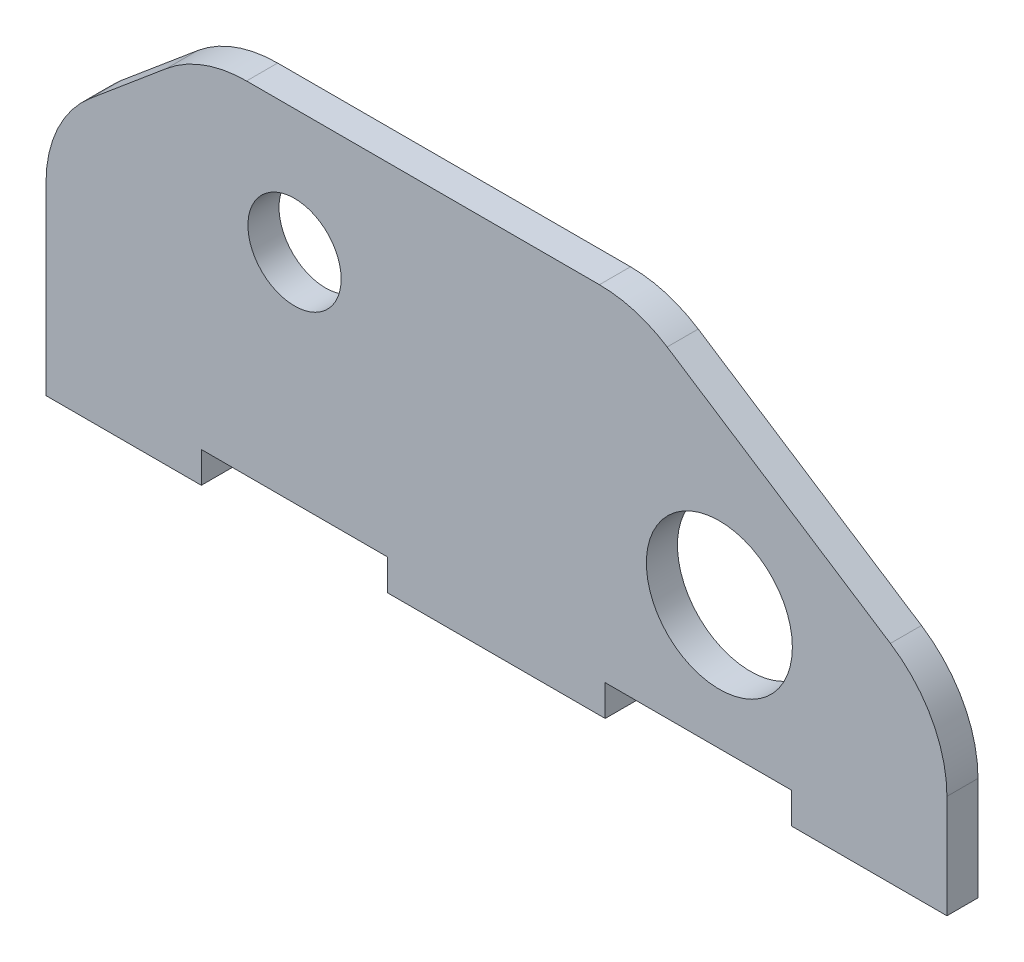
SolidWorks part; units mm, degrees
ref_plane "Plan de face" through (0, 0, 0) normal (0, 0, 1) x (1, 0, 0)
ref_plane "Plan de dessus" through (0, 0, 0) normal (0, 1, 0) x (1, 0, 0)
ref_plane "Plan de droite" through (0, 0, 0) normal (1, 0, 0) x (0, 0, -1)
sketch "Esquisse1" plane through (0, 0, 0) normal (0, 0, 1) x (1, 0, 0)
  line L0 (0, 0) -> (290, 0) construction
  line L1 (290, 0) -> (290, 55)
  line L2 (290, 90) -> (260, 120) construction
  line L3 (260, 120) -> (190, 170) construction
  line L4 (190, 170) -> (50, 120) construction
  line L5 (0, 90) -> (0, 0) construction
  line L6 (0, 90) -> (290, 90) construction
  line L7 (50, 120) -> (0, 90) construction
  line L8 (50, 120) -> (50, 90) construction
  line L9 (190, 170) -> (190, 90) construction
  line L10 (260, 120) -> (190, 120) construction
  line L11 (260, 120) -> (260, 90) construction
  line L12 (0, 0) -> (50, 0)
  line L13 (50, 0) -> (50, 10)
  line L14 (50, 10) -> (110, 10)
  line L15 (110, 10) -> (110, 0)
  line L16 (110, 0) -> (180, 0)
  line L17 (180, 0) -> (180, 10)
  line L18 (180, 10) -> (240, 10)
  line L19 (240, 10) -> (240, 0)
  line L20 (240, 0) -> (290, 0)
  line L21 (145, 0) -> (145, 90) construction
  line L22 (50, 120) -> (190, 120)
  line L23 (0, 10) -> (290, 10) construction
  line L24 (50, 120) -> (0, 78.045)
  line L25 (0, 0) -> (0, 78.045)
  line L26 (290, 55) -> (190, 120)
  line L27 (290, 90) -> (290, 55) construction
  circle A0 centre (80, 80) radius 15
  circle A1 centre (216.7479, 50) radius 23.5
  dimension "D6" = 30
  dimension "D7" = 30
  dimension "D8" = 80
  dimension "D5" = 290
  dimension "D12" = 47
  dimension "D3" = 30
  dimension "D1" = 90
  dimension "D2" = 10
  dimension "D4" = 100
  dimension "D9" = 60
  dimension "D10" = 60
  dimension "D11" = 70
  dimension "D13" = 80
  dimension "D14" = 140
  dimension "D15" = 40
  dimension "D16" = 40
  dimension "D17" = 30
  dimension "D18" = 50
  dimension "D19" = 5
extrude "Boss.-Extru.1" add sketch "Esquisse1" along normal blind 10
fillet "Congé1" radius 40 4 edges at (0, 78.045, 5) (290, 55, 5) (190, 120, 5) (50, 120, 5)
